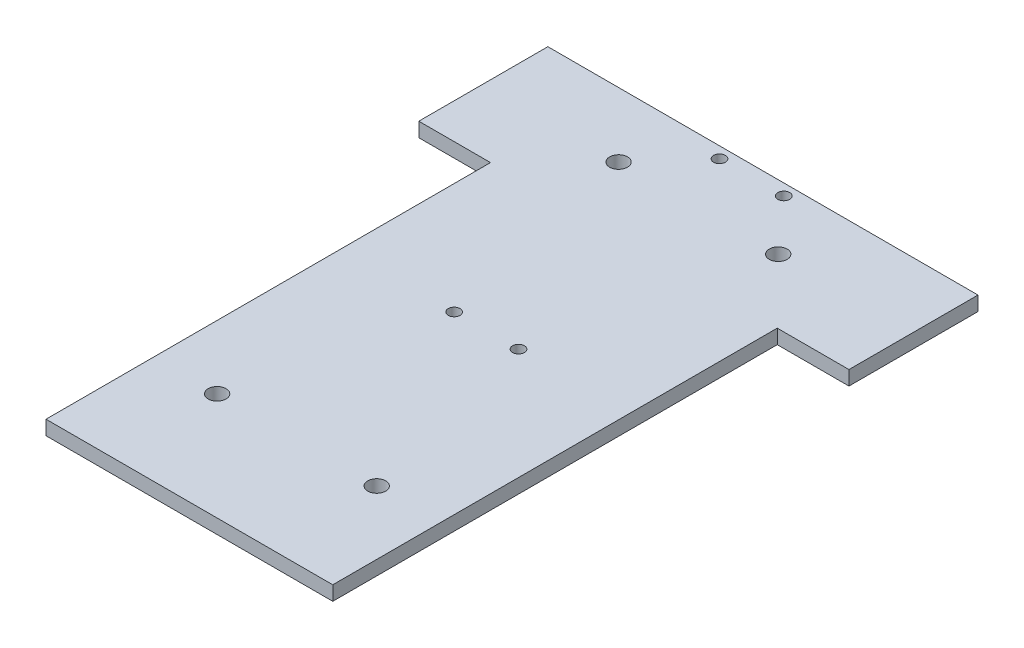
SolidWorks part; units mm, degrees
ref_plane "Front Plane" through (0, 0, 0) normal (0, 0, 1) x (1, 0, 0)
ref_plane "Top Plane" through (0, 0, 0) normal (0, 1, 0) x (1, 0, 0)
ref_plane "Right Plane" through (0, 0, 0) normal (1, 0, 0) x (0, 0, -1)
sketch "Sketch1" plane through (0, 0, 0) normal (0, 1, 0) x (1, 0, 0)
  line L0 (0, 0) -> (12.7, 0) construction
  line L1 (0, 101.6) -> (76.2, 101.6)
  line L2 (0, 101.6) -> (0, 78.74)
  line L3 (12.7, 0) -> (63.5, 0)
  line L4 (76.2, 101.6) -> (76.2, 78.74)
  line L5 (76.2, 0) -> (63.5, 0) construction
  line L6 (76.2, 0) -> (76.2, 78.74) construction
  line L7 (76.2, 78.74) -> (63.5, 78.74)
  line L8 (63.5, 0) -> (63.5, 78.74)
  line L9 (0, 0) -> (12.7, 0) construction
  line L10 (0, 0) -> (0, 78.74) construction
  line L11 (0, 78.74) -> (12.7, 78.74)
  line L12 (12.7, 0) -> (12.7, 78.74)
  line L13 (0, 78.74) -> (0, 0) construction
  line L14 (63.5, 0) -> (76.2, 0) construction
  line L15 (76.2, 78.74) -> (76.2, 0) construction
  dimension "D1" = 101.6
  dimension "D2" = 76.2
  dimension "D3" = 12.7
  dimension "D4" = 12.7
  dimension "D5" = 22.86
extrude "Boss-Extrude1" add sketch "Sketch1" along normal blind 2.54
sketch "Sketch2" plane through (0, 2.54, 0) normal (0, 1, 0) x (1, 0, 0)
  circle A3 centre (32.4, 52.6) radius 1.05
  circle A4 centre (43.8, 52.6) radius 1.05
  circle A5 centre (43.8, 99.6) radius 1.05
  circle A6 centre (32.4, 99.6) radius 1.05
  arc A7 (32.4, 98.55) -> (32.4, 100.65) centre (32.4, 99.6) ccw construction
  arc A9 (43.8, 100.65) -> (43.8, 98.55) centre (43.8, 99.6) ccw construction
  arc A10 (43.8, 53.65) -> (43.8, 51.55) centre (43.8, 52.6) ccw construction
  arc A11 (32.4, 51.55) -> (32.4, 53.65) centre (32.4, 52.6) ccw construction
extrude "Cut-Extrude1" cut sketch "Sketch2" against normal up to next
sketch "Sketch3" plane through (0, 0, 0) normal (0, -1, 0) x (-1, 0, 0)
  circle A0 centre (-23.9621, 19.05) radius 1.5875
  circle A1 centre (-23.9621, 19.05) radius 1.5875 construction
  circle A2 centre (-52.2379, 19.05) radius 1.5875
  circle A3 centre (-23.9621, 90.17) radius 1.5875
  circle A4 centre (-52.2379, 90.17) radius 1.5875
  circle A5 centre (-52.2379, 19.05) radius 1.5875 construction
  circle A6 centre (-23.9621, 90.17) radius 1.5875 construction
  circle A7 centre (-52.2379, 90.17) radius 1.5875 construction
extrude "Cut-Extrude2" cut sketch "Sketch3" against normal up to next
